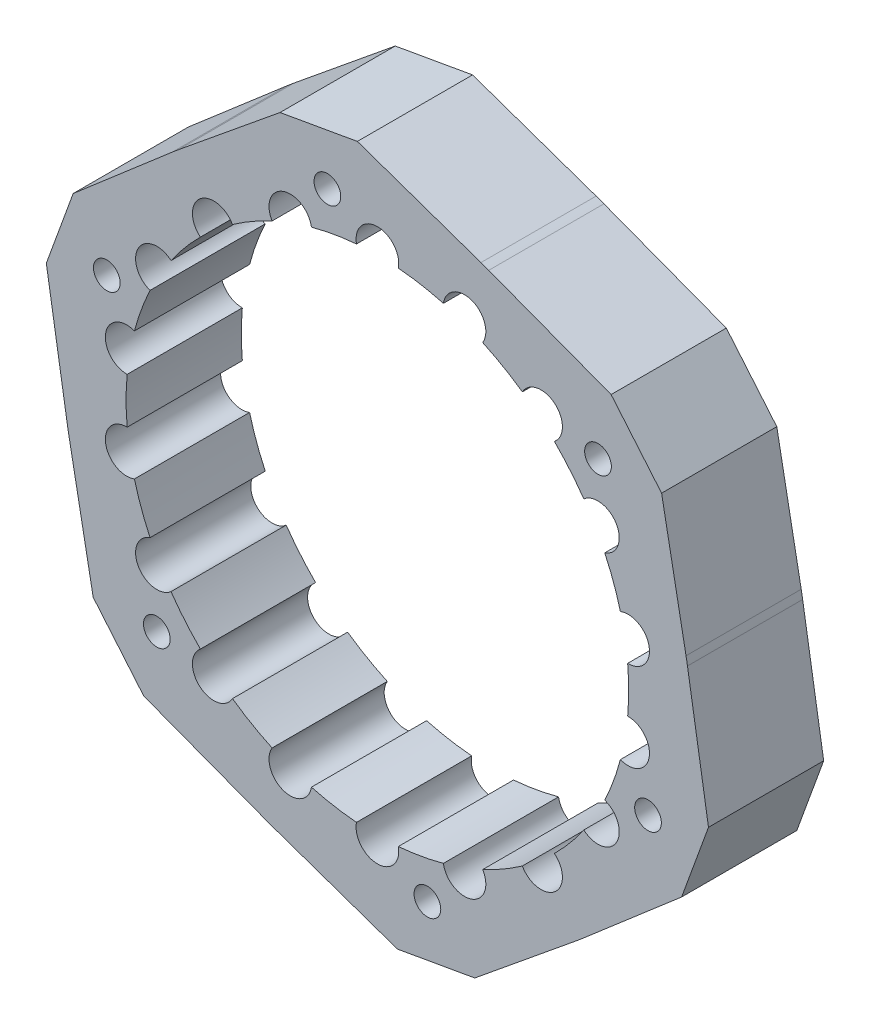
SolidWorks part; units mm, degrees
ref_plane "Front Plane" through (0, 0, 0) normal (0, 0, 1) x (1, 0, 0)
ref_plane "Top Plane" through (0, 0, 0) normal (0, 1, 0) x (1, 0, 0)
ref_plane "Right Plane" through (0, 0, 0) normal (1, 0, 0) x (0, 0, -1)
sketch "Sketch1" plane through (0, 0, 0) normal (0, 0, 1) x (1, 0, 0)
  arc A1 (3.9965, 47.8333) -> (-3.9965, 47.8333) centre (0, 48.6292) ccw
  circle A2 centre (0, 0) radius 60
  arc A4 (20.1155, 43.5817) -> (12.6045, 46.3155) centre (16.6322, 45.6965) ccw
  arc A6 (33.8082, 34.0735) -> (27.6852, 39.2114) centre (31.2582, 37.2521) ccw
  arc A8 (43.4231, 20.4556) -> (39.4266, 27.3778) centre (42.1141, 24.3146) ccw
  arc A10 (47.8006, 4.3704) -> (46.4126, 12.242) centre (47.8904, 8.4444) ccw
  arc A12 (46.4126, -12.242) -> (47.8006, -4.3704) centre (47.8904, -8.4444) ccw
  arc A14 (39.4266, -27.3778) -> (43.4231, -20.4556) centre (42.1141, -24.3146) ccw
  arc A16 (27.6852, -39.2114) -> (33.8082, -34.0735) centre (31.2582, -37.2521) ccw
  arc A18 (12.6045, -46.3155) -> (20.1155, -43.5817) centre (16.6322, -45.6965) ccw
  arc A20 (-3.9965, -47.8333) -> (3.9965, -47.8333) centre (0, -48.6292) ccw
  arc A22 (-20.1155, -43.5817) -> (-12.6045, -46.3155) centre (-16.6322, -45.6965) ccw
  arc A24 (-33.8082, -34.0735) -> (-27.6852, -39.2114) centre (-31.2582, -37.2521) ccw
  arc A26 (-43.4231, -20.4556) -> (-39.4266, -27.3778) centre (-42.1141, -24.3146) ccw
  arc A28 (-47.8006, -4.3704) -> (-46.4126, -12.242) centre (-47.8904, -8.4444) ccw
  arc A30 (-46.4126, 12.242) -> (-47.8006, 4.3704) centre (-47.8904, 8.4444) ccw
  arc A32 (-39.4266, 27.3778) -> (-43.4231, 20.4556) centre (-42.1141, 24.3146) ccw
  arc A34 (-27.6852, 39.2114) -> (-33.8082, 34.0735) centre (-31.2582, 37.2521) ccw
  arc A36 (-12.6045, 46.3155) -> (-20.1155, 43.5817) centre (-16.6322, 45.6965) ccw
  arc A38 (-33.8082, 34.0735) -> (-39.4266, 27.3778) centre (0, 0) ccw
  arc A41 (-20.1155, 43.5817) -> (-27.6852, 39.2114) centre (0, 0) ccw
  arc A42 (-3.9965, 47.8333) -> (-12.6045, 46.3155) centre (0, 0) ccw
  arc A43 (12.6045, 46.3155) -> (3.9965, 47.8333) centre (0, 0) ccw
  arc A44 (27.6852, 39.2114) -> (20.1155, 43.5817) centre (0, 0) ccw
  arc A45 (39.4266, 27.3778) -> (33.8082, 34.0735) centre (0, 0) ccw
  arc A46 (46.4126, 12.242) -> (43.4231, 20.4556) centre (0, 0) ccw
  arc A47 (47.8006, -4.3704) -> (47.8006, 4.3704) centre (0, 0) ccw
  arc A48 (43.4231, -20.4556) -> (46.4126, -12.242) centre (0, 0) ccw
  arc A49 (33.8082, -34.0735) -> (39.4266, -27.3778) centre (0, 0) ccw
  arc A50 (20.1155, -43.5817) -> (27.6852, -39.2114) centre (0, 0) ccw
  arc A51 (3.9965, -47.8333) -> (12.6045, -46.3155) centre (0, 0) ccw
  arc A52 (-12.6045, -46.3155) -> (-3.9965, -47.8333) centre (0, 0) ccw
  arc A53 (-27.6852, -39.2114) -> (-20.1155, -43.5817) centre (0, 0) ccw
  arc A54 (-39.4266, -27.3778) -> (-33.8082, -34.0735) centre (0, 0) ccw
  arc A55 (-46.4126, -12.242) -> (-43.4231, -20.4556) centre (0, 0) ccw
  arc A56 (-47.8006, 4.3704) -> (-47.8006, -4.3704) centre (0, 0) ccw
  arc A57 (-43.4231, 20.4556) -> (-46.4126, 12.242) centre (0, 0) ccw
  point P59 (0, 0)
  dimension "D1" = 48
  dimension "D2" = 8.15
  dimension "D3" = 120
  dimension "D5" = 3.9965
  dimension "D4" = 18
extrude "Boss-Extrude1" add sketch "Sketch1" along normal blind 22
sketch "Sketch2" plane through (0, 0, 22) normal (0, 0, 1) x (1, 0, 0)
  line L0 (0, 0) -> (0, 60) construction
  line L1 (0, 0) -> (-9.5506, 54.1644) construction
  circle A0 centre (0, 0) radius 55 construction
  circle A1 centre (-9.5506, 54.1644) radius 2.55
  circle A2 centre (0, 0) radius 60 construction
  circle A3 centre (42.1324, 35.3533) radius 2.55
  circle A4 centre (51.6831, -18.8111) radius 2.55
  circle A5 centre (9.5506, -54.1644) radius 2.55
  circle A6 centre (-42.1324, -35.3533) radius 2.55
  circle A7 centre (-51.6831, 18.8111) radius 2.55
  point P22 (0, 0)
  dimension "D1" = 110
  dimension "D2" = 5.1
  dimension "D3" = 10
  dimension "D4" = 6
extrude "Cut-Extrude2" cut sketch "Sketch2" against normal through all
sketch "Sketch3" plane through (0, 0, 22) normal (0, 0, 1) x (1, 0, 0)
  line L0 (0, 0) -> (-9.5506, 54.1644) construction
  line L1 (-9.5506, 54.1644) -> (-11.2871, 64.0125) construction
  line L2 (0, 65) -> (0, 0) construction
  line L3 (-37.9588, 46.4664) -> (-18.5978, 62.2826)
  line L4 (-18.5978, 62.2826) -> (-3.8257, 64.8873)
  line L5 (-3.8257, 64.8873) -> (19.7772, 56.6468)
  line L6 (54.2812, 35.7568) -> (58.9462, 11.1959)
  line L7 (44.6394, 47.2475) -> (54.2812, 35.7568)
  line L8 (21.2617, 56.1065) -> (44.6394, 47.2475)
  line L9 (58.1069, -29.1305) -> (39.169, -45.4509)
  line L10 (63.2372, -15.0351) -> (58.1069, -29.1305)
  line L11 (59.2205, 9.6401) -> (63.2372, -15.0351)
  line L12 (3.8257, -64.8873) -> (-19.7772, -56.6468)
  line L13 (18.5978, -62.2826) -> (3.8257, -64.8873)
  line L14 (37.9588, -46.4664) -> (18.5978, -62.2826)
  line L15 (-54.2812, -35.7568) -> (-58.9462, -11.1959)
  line L16 (-44.6394, -47.2475) -> (-54.2812, -35.7568)
  line L17 (-21.2617, -56.1065) -> (-44.6394, -47.2475)
  line L18 (-58.1069, 29.1305) -> (-39.169, 45.4509)
  line L19 (-63.2372, 15.0351) -> (-58.1069, 29.1305)
  line L20 (-59.2205, -9.6401) -> (-63.2372, 15.0351)
  circle A0 centre (0, 0) radius 65 construction
  circle A1 centre (0, 0) radius 60 construction
  arc A2 (-37.9588, 46.4664) -> (19.7772, 56.6468) centre (0, 0) cw
  arc A3 (21.2617, 56.1065) -> (58.9462, 11.1959) centre (0, 0) cw
  arc A4 (59.2205, 9.6401) -> (39.169, -45.4509) centre (0, 0) cw
  arc A5 (37.9588, -46.4664) -> (-19.7772, -56.6468) centre (0, 0) cw
  arc A6 (-21.2617, -56.1065) -> (-58.9462, -11.1959) centre (0, 0) cw
  arc A7 (-59.2205, -9.6401) -> (-39.169, 45.4509) centre (0, 0) cw
  point P11 (-11.2117, 63.585)
  point P38 (0, 0)
  dimension "D1" = 130
  dimension "D2" = 15
  dimension "D3" = 6
extrude "Boss-Extrude2" add sketch "Sketch3" against normal blind 22
